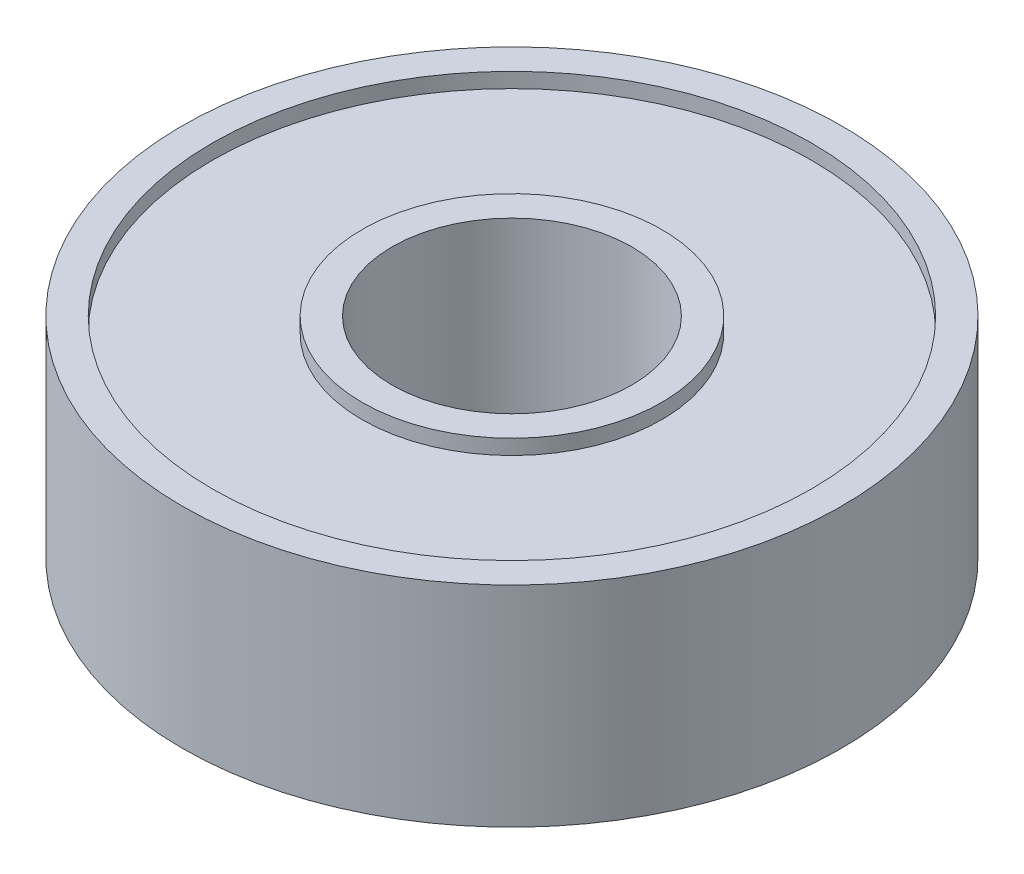
SolidWorks part; units mm, degrees
ref_plane "Front Plane" through (0, 0, 0) normal (0, 0, 1) x (1, 0, 0)
ref_plane "Top Plane" through (0, 0, 0) normal (0, 1, 0) x (1, 0, 0)
ref_plane "Right Plane" through (0, 0, 0) normal (1, 0, 0) x (0, 0, -1)
sketch "Sketch2" plane through (0, 0, 0) normal (0, 1, 0) x (1, 0, 0)
  circle A0 centre (0, 0) radius 11
  circle A1 centre (0, 0) radius 4
  dimension "D1" = 8
  dimension "D2" = 22
extrude "Boss-Extrude1" add sketch "Sketch2" along normal blind 7
sketch "Sketch3" plane through (0, 7, 0) normal (0, 1, 0) x (1, 0, 0)
  circle A1 centre (0, 0) radius 5
  circle A2 centre (0, 0) radius 10
  circle A3 centre (0, 0) radius 10
  circle A4 centre (0, 0) radius 4 construction
  dimension "D2" = 1
  dimension "D1" = 1
extrude "Cut-Extrude1" cut sketch "Sketch3" against normal blind 0.5
ref_plane "Plane1" through (0, 3.5, 0) normal (0, 1, 0) x (1, 0, 0)
mirror "Mirror1" about plane through (0, 3.5, 0) normal (0, 1, 0) of "Cut-Extrude1"
